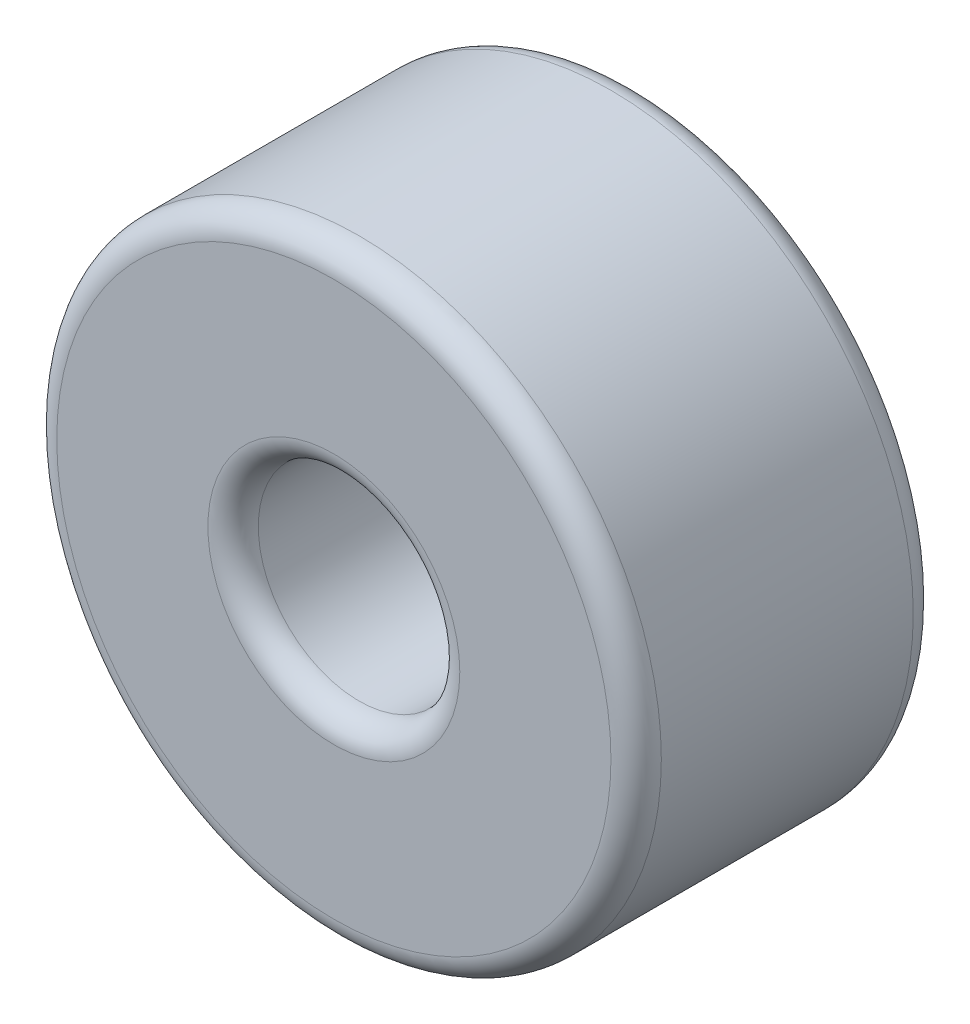
SolidWorks part; units mm, degrees
ref_plane "Front Plane" through (0, 0, 0) normal (0, 0, 1) x (1, 0, 0)
ref_plane "Top Plane" through (0, 0, 0) normal (0, 1, 0) x (1, 0, 0)
ref_plane "Right Plane" through (0, 0, 0) normal (1, 0, 0) x (0, 0, -1)
sketch "Sketch1" plane through (0, 0, 0) normal (0, 0, 1) x (1, 0, 0)
  circle A0 centre (0, 0) radius 1
  dimension "D1" = 2
extrude "Extrude-Thin1" add sketch "Sketch1" along normal blind 3 thin
fillet "Fillet1" radius 0.25 4 edges at (1, 0, 0) (3, 0, 0) (1, 0, 3) (3, 0, 3)
